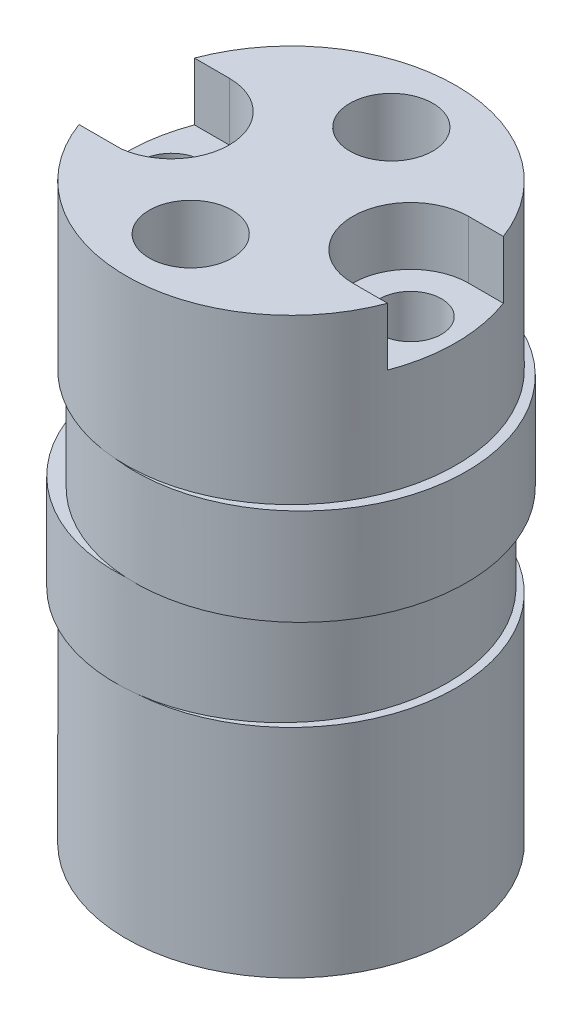
SolidWorks part; units mm, degrees
material "Like ABS"
ref_plane "Front Plane" through (0, 0, 0) normal (0, 0, 1) x (1, 0, 0)
ref_plane "Top Plane" through (0, 0, 0) normal (0, 1, 0) x (1, 0, 0)
ref_plane "Right Plane" through (0, 0, 0) normal (1, 0, 0) x (0, 0, -1)
sketch "Sketch1" plane through (0, 0, 0) normal (0, 1, 0) x (1, 0, 0)
  circle A0 centre (0, 0) radius 8.6
  dimension "D1" = 17.2
extrude "Boss-Extrude11" add sketch "Sketch1" along normal blind 5
sketch "Sketch20" plane through (0, 5, 0) normal (0, 1, 0) x (1, 0, 0)
  line L0 (0, 0) -> (1, 0) construction
  circle A0 centre (1, 0) radius 8.6
  dimension "D2" = 17.2
  dimension "D1" = 1
extrude "Boss-Extrude12" add sketch "Sketch20" along normal blind 5
sketch "Sketch21" plane through (0, 10, 0) normal (0, 1, 0) x (1, 0, 0)
  line L0 (0, 0) -> (0.5, 0) construction
  circle A0 centre (0.5, 0) radius 8.55
  dimension "D2" = 17.1
  dimension "D1" = 0.5
extrude "Boss-Extrude13" add sketch "Sketch21" along normal blind 1
sketch "Sketch22" plane through (0, 11, 0) normal (0, 1, 0) x (1, 0, 0)
  line L0 (0, 0) -> (0.5, 0) construction
  circle A0 centre (0.5, 0) radius 8.55
  dimension "D2" = 17.1
  dimension "D1" = 0.5
extrude "Boss-Extrude14" add sketch "Sketch22" along normal blind 7.5
sketch "Sketch24" plane through (0, 18.5, 0) normal (0, 1, 0) x (1, 0, 0)
  line L0 (0, 0) -> (0.7, 0) construction
  line L1 (0.7, 0) -> (0.7, 5) construction
  circle A0 centre (0.7, 5) radius 2.15
  dimension "D3" = 4.3
  dimension "D1" = 0.7
  dimension "D2" = 5
extrude "Cut-Extrude8" cut sketch "Sketch24" against normal blind 7
sketch "Sketch30" plane through (0, 0, 0) normal (0, -1, 0) x (1, 0, 0)
  line L0 (0, 0) -> (0.5, 0) construction
  circle A1 centre (0.5, 0) radius 8.55
  dimension "D1" = 0.5
  dimension "D2" = 17.1
extrude "Boss-Extrude15" add sketch "Sketch30" along normal blind 11.25
sketch "Sketch31" plane through (0, 18.5, 0) normal (0, 1, 0) x (1, 0, 0)
  line L0 (0, 0) -> (0.7, 0) construction
  line L1 (0.7, 0) -> (6.7, 0) construction
  circle A0 centre (6.7, 0) radius 1.6
  dimension "D3" = 3.2
  dimension "D1" = 0.7
  dimension "D2" = 6
extrude "Cut-Extrude12" cut sketch "Sketch31" against normal up to surface (29.75 mm away) up to face at (0.5, -11.25, -8.55)
sketch "Sketch32" plane through (0, 11.5, 0) normal (0, 1, 0) x (1, 0, 0)
  circle A0 centre (0.7, 5) radius 1.5
  dimension "D1" = 3
extrude "Cut-Extrude13" cut sketch "Sketch32" against normal up to surface (22.75 mm away) up to face at (6.7, -11.25, -1.6)
pattern_circular "CirPattern7" count 2 over 360 about axis through (0.5, 0, 0) along (0, 1, 0) of "Cut-Extrude12"
pattern_circular "CirPattern8" count 2 over 360 about axis through (0.5, 0, 0) along (0, 1, 0) of "Cut-Extrude8", "Cut-Extrude13"
sketch "Sketch33" plane through (0, -11.25, 0) normal (0, -1, 0) x (1, 0, 0)
  line L0 (0, 0) -> (0.7, 0) construction
  circle A0 centre (0.7, 0) radius 2.1
  dimension "D2" = 4.2
  dimension "D1" = 0.7
extrude "Cut-Extrude14" cut sketch "Sketch33" against normal blind 5.8
sketch "Sketch34" plane through (0, 18.5, 0) normal (0, 1, 0) x (1, 0, 0)
  line L1 (-5.7, 3) -> (-9.0544, 3)
  line L3 (-5.3035, -2.9737) -> (-9.0544, -2.9737)
  line L4 (-9.0544, 3) -> (-9.0544, -2.9737)
  line L5 (6.7, 3) -> (10.1136, 3)
  line L7 (6.7, -3) -> (10.1136, -3)
  line L8 (10.1136, 3) -> (10.1136, -3)
  arc A0 (-5.3035, -2.9737) -> (-5.7, 3) centre (-5.7, 0) ccw
  arc A1 (6.7, 3) -> (6.7, -3) centre (6.7, 0) ccw
  dimension "D1" = 6
extrude "Cut-Extrude15" cut sketch "Sketch34" against normal blind 3
